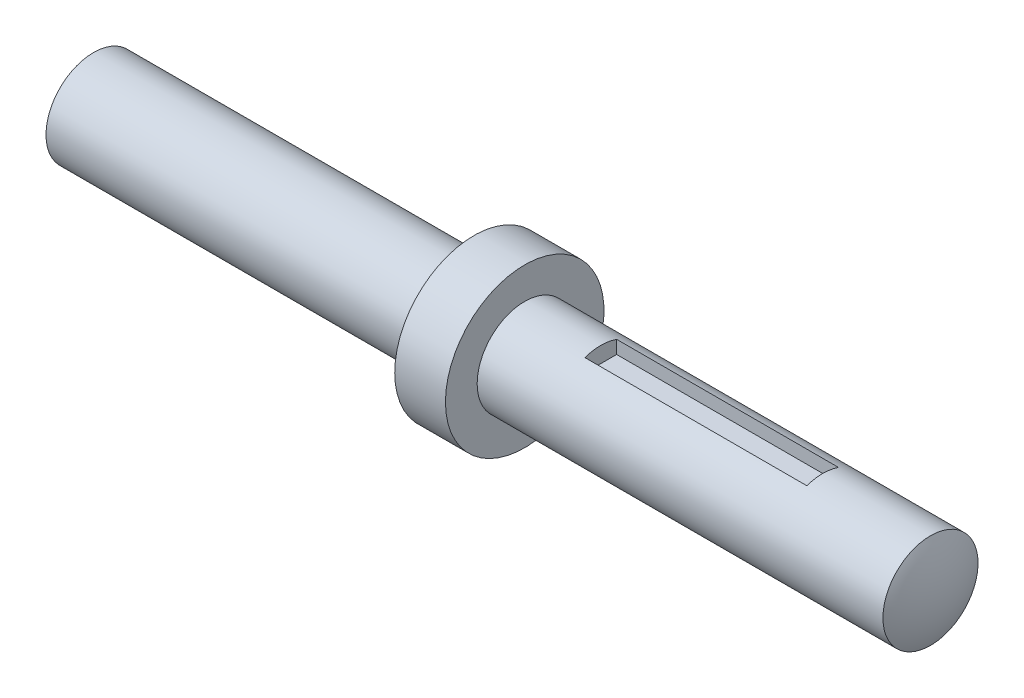
SolidWorks part; units mm, degrees
ref_plane "Front Plane" through (0, 0, 0) normal (0, 0, 1) x (1, 0, 0)
ref_plane "Top Plane" through (0, 0, 0) normal (0, 1, 0) x (1, 0, 0)
ref_plane "Right Plane" through (0, 0, 0) normal (1, 0, 0) x (0, 0, -1)
sketch "Sketch1" plane through (0, 0, 0) normal (0, 0, 1) x (1, 0, 0)
  line L0 (-80.6849, 0) -> (121.2321, 0) construction
  line L1 (-64, 0) -> (-64, 7.5)
  line L2 (-64, 7.5) -> (-4, 7.5)
  line L3 (-4, 7.5) -> (-4, 12.5)
  line L4 (-4, 12.5) -> (4, 12.5)
  line L5 (4, 12.5) -> (4, 7.5)
  line L6 (4, 7.5) -> (68, 7.5)
  line L7 (68, 7.5) -> (68, 0)
  line L8 (-65.7705, 0) -> (-64, 0)
  line L9 (69.7705, 0) -> (68, 0)
  arc A0 (-64, 7.5) -> (-65.7705, 0) centre (-49, 0) ccw
  arc A2 (69.7705, 0) -> (68, 7.5) centre (53, 0) ccw
  point P5 (0, 12.5)
  dimension "D1" = 7.5
  dimension "D7" = 15
  dimension "D2" = 60
  dimension "D3" = 8
  dimension "D4" = 132
  dimension "D5" = 7.5
  dimension "D6" = 12.5
  dimension "D8" = 15
revolve "Revolve1" add sketch "Sketch1" angle 360 about L0
sketch "Sketch2" plane through (0, 0, 0) normal (0, 0, 1) x (1, 0, 0)
  line L0 (51, 10) -> (51, 5)
  line L1 (51, 5) -> (16, 5)
  line L2 (16, 5) -> (16, 9.65)
  line L3 (16, 9.65) -> (51, 10)
  line L4 (68, 7.5) -> (4, 7.5) construction
  line L5 (4, -12.5) -> (4, 12.5) construction
  dimension "D1" = 5
  dimension "D2" = 35
  dimension "D3" = 4.65
  dimension "D4" = 2.5
  dimension "D5" = 12
extrude "Cut-Extrude1" cut sketch "Sketch2" against normal mid plane 5
